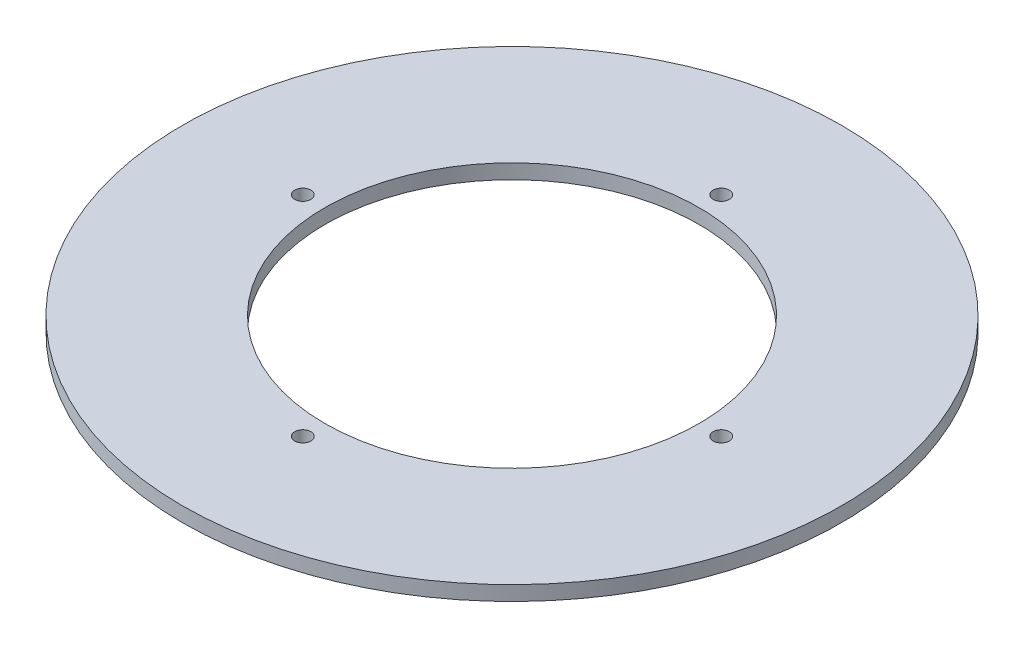
SolidWorks part; units mm, degrees
ref_plane "Front Plane" through (0, 0, 0) normal (0, 0, 1) x (1, 0, 0)
ref_plane "Top Plane" through (0, 0, 0) normal (0, 1, 0) x (1, 0, 0)
ref_plane "Right Plane" through (0, 0, 0) normal (1, 0, 0) x (0, 0, -1)
sketch "Croquis1" plane through (0, 0, 0) normal (0, 1, 0) x (1, 0, 0)
  line L0 (0, 58) -> (0, -58) construction
  line L2 (58, 0) -> (-58, 0) construction
  circle A0 centre (0, 0) radius 51.86
  circle A1 centre (0, 0) radius 91.36
  circle A2 centre (0, 0) radius 58 construction
  circle A3 centre (-58, 0) radius 2.25
  circle A4 centre (0, 58) radius 2.25
  circle A5 centre (58, 0) radius 2.25
  circle A6 centre (0, -58) radius 2.25
  dimension "D1" = 103.72
  dimension "D2" = 4.5
  dimension "D3" = 6.14
  dimension "D4" = 39.5
extrude "Saliente-Extruir1" add sketch "Croquis1" along normal blind 4.06
